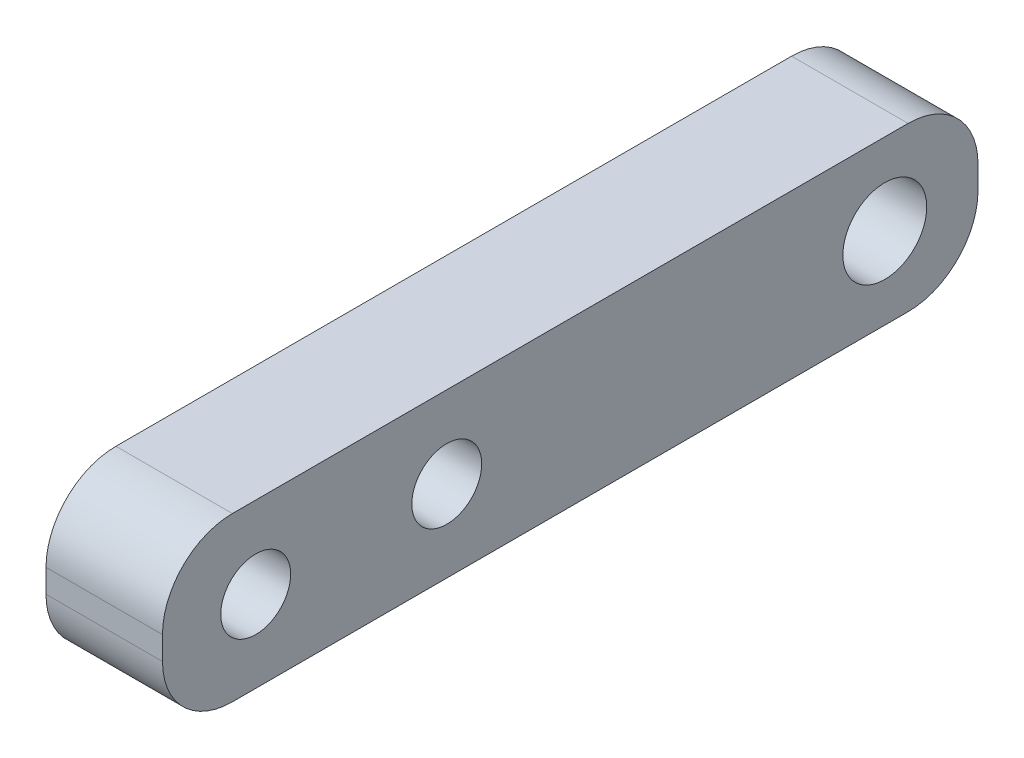
SolidWorks part; units mm, degrees
ref_plane "Front" through (0, 0, 0) normal (0, 0, 1) x (1, 0, 0)
ref_plane "Top" through (0, 0, 0) normal (0, 1, 0) x (1, 0, 0)
ref_plane "Right" through (0, 0, 0) normal (1, 0, 0) x (0, 0, -1)
sketch "Sketch1" plane through (0, 0, 0) normal (1, 0, 0) x (0, 0, -1)
  line L1 (0, 0) -> (35, 0)
  line L2 (0, 0) -> (0, -7)
  line L3 (0, -7) -> (35, -7)
  line L4 (35, 0) -> (35, -7)
  dimension "D1" = 7
  dimension "D2" = 35
extrude "Boss-Extrude1" add sketch "Sketch1" along normal blind 5
sketch "Sketch2" plane through (5, 0, 0) normal (1, 0, 0) x (0, 0, -1)
  line L0 (35, 0) -> (0, 0) construction
  line L1 (0, 0) -> (0, -7) construction
  line L2 (35, -7) -> (35, 0) construction
  circle A0 centre (4, -3.5) radius 1.5
  circle A1 centre (12.2, -3.5) radius 1.5
  circle A2 centre (31, -3.5) radius 1.8
  dimension "D1" = 3
  dimension "D2" = 3
  dimension "D3" = 3.6
  dimension "D4" = 3.5
  dimension "D5" = 3.5
  dimension "D6" = 3.5
  dimension "D7" = 4
  dimension "D8" = 4
  dimension "D9" = 22.8
extrude "Cut-Extrude1" cut sketch "Sketch2" against normal through all
fillet "Fillet1" radius 3 4 edges at (2.5, -7, -35) (2.5, 0, -35) (2.5, 0, 0) (2.5, -7, 0)
equation "\"滑动-垂直孔\" = 0.6"
equation "\"滑动-水平孔\"= 0.3"
equation "\"松动-垂直孔\" = 0.3"
equation "\"松动-水平孔\"= 0.1"
equation "\"正常-垂直孔\" = 0.15"
equation "\"正常-水平孔\"= 0"
equation "\"紧缩-垂直孔\"= 0"
equation "\"紧缩-水平孔\"= - 0.1"
equation "\"D3@Sketch2\"=\"滑动-垂直孔\"+3"
equation "\"D2@Sketch2\"=\"紧缩-垂直孔\"+3"
equation "\"D1@Sketch2\"=\"紧缩-垂直孔\"+3"
